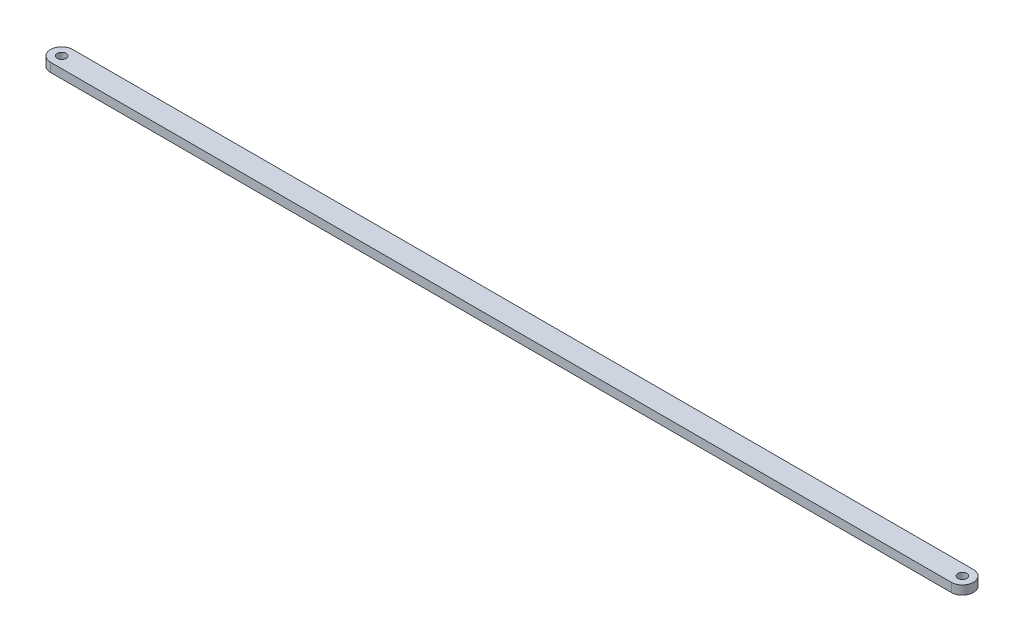
SolidWorks part; units mm, degrees
material "Brass"
ref_plane "Front Plane" through (0, 0, 0) normal (0, 0, 1) x (1, 0, 0)
ref_plane "Top Plane" through (0, 0, 0) normal (0, 1, 0) x (1, 0, 0)
ref_plane "Right Plane" through (0, 0, 0) normal (1, 0, 0) x (0, 0, -1)
sketch "Sketch1" plane through (0, 0, 0) normal (0, 1, 0) x (1, 0, 0)
  line L0 (-203.5, 0) -> (203.5, 0) construction
  line L1 (-203.5, 5) -> (203.5, 5)
  line L2 (-203.5, -5) -> (203.5, -5)
  line L3 (0, 0) -> (0, 18.1813) construction
  arc A0 (-203.5, 5) -> (-203.5, -5) centre (-203.5, 0) ccw
  arc A1 (203.5, -5) -> (203.5, 5) centre (203.5, 0) ccw
  circle A2 centre (203.5, 0) radius 2
  circle A3 centre (-203.5, 0) radius 2
  point P2 (0, 0)
  dimension "D3" = 4
  dimension "D1" = 407
  dimension "D2" = 10
extrude "Boss-Extrude1" add sketch "Sketch1" along normal mid plane 4
